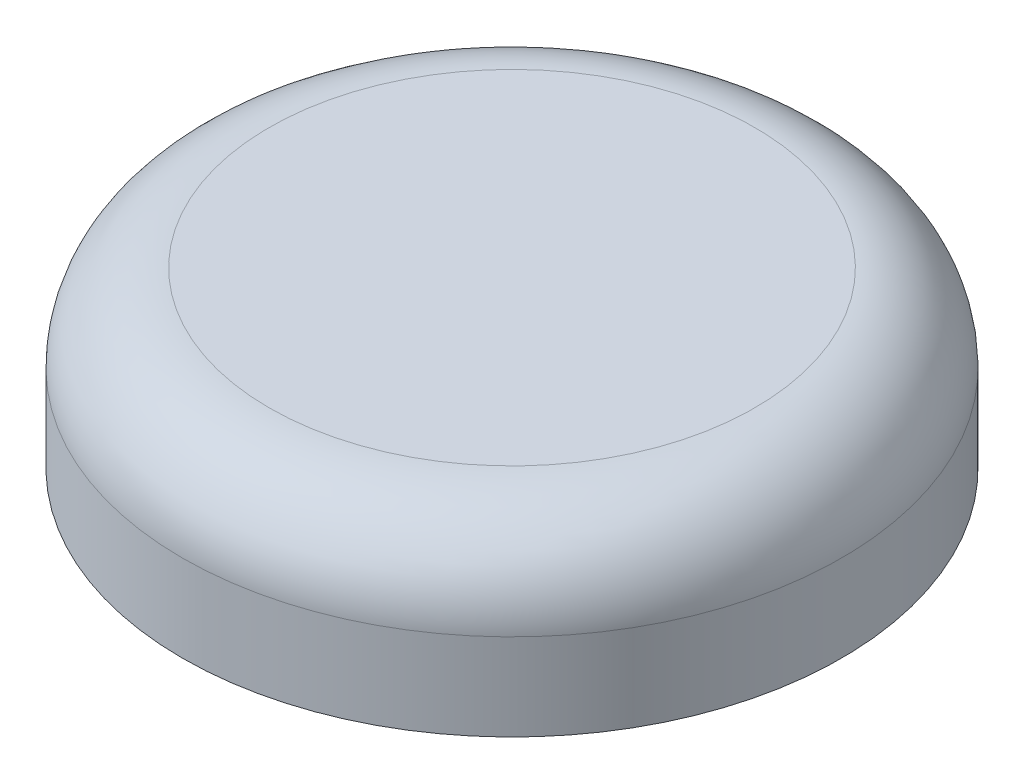
SolidWorks part; units mm, degrees
ref_plane "Front Plane" through (0, 0, 0) normal (0, 0, 1) x (1, 0, 0)
ref_plane "Top Plane" through (0, 0, 0) normal (0, 1, 0) x (1, 0, 0)
ref_plane "Right Plane" through (0, 0, 0) normal (1, 0, 0) x (0, 0, -1)
sketch "Sketch1" plane through (0, 0, 0) normal (0, 1, 0) x (1, 0, 0)
  circle A0 centre (0, 0) radius 28.5
  dimension "D1" = 57
extrude "Boss-Extrude1" add sketch "Sketch1" along normal blind 15
fillet "Fillet1" radius 7.5 1 edges at (0, 15, 28.5)
sketch "Sketch2" plane through (0, 0, 0) normal (0, 1, 0) x (1, 0, 0)
  line L0 (-25.204, 0) -> (24.9636, 0) construction
  line L1 (-16.25, 16.25) -> (16.25, 16.25)
  line L2 (-16.25, 16.25) -> (-16.25, -16.25)
  line L3 (-16.25, -16.25) -> (16.25, -16.25)
  line L4 (16.25, 16.25) -> (16.25, -16.25)
  line L5 (0, 23.5211) -> (0, -23.6012) construction
  point P9 (16.25, 0)
  point P10 (0, 16.25)
  point P11 (0, 0)
  point P12 (0, 0)
  point P13 (0, 0)
  point P14 (0, 0)
  point P15 (0, 0)
  point P16 (0, 0)
  point P17 (0, 0)
  point P18 (0, 0)
  point P19 (0, 0)
  dimension "D1" = 32.5
  dimension "D2" = 32.5
hole_wizard "#32 (0.116) Diameter Hole4" positions "Sketch12" profile "Sketch13" hole size "#32" standard "ANSI Inch"
sketch "Sketch12" plane through (0, 0, 0) normal (0, -1, 0) x (-1, 0, 0)
  point P0 (-16.25, 16.25)
  point P3 (16.25, 16.25)
  point P6 (16.25, -16.25)
  point P9 (-16.25, -16.25)
sketch "Sketch13" plane through (16.25, 0, -16.25) normal (1, 0, 0) x (0, 0, -1)
  line L0 (0, 0) -> (0, 3.8852)
  line L1 (0, 3.8852) -> (1.4732, 3)
  line L2 (1.4732, 3) -> (1.4732, 0)
  line L5 (1.4732, 0) -> (0, 0)
  line L10 (0, 3.8852) -> (-1.4732, 3) construction
  line L11 (0, -6.35) -> (0, 107.95) construction
  dimension "Hole Dia." = 2.9464
  dimension "Hole Depth" = 3
  dimension "Drill Angle" = 118
thread "Thread6" pitch 0.7937 start angle 0, offset 1, length 4, pitch 0.7937, diameter 2.9464
ref_plane "Plane10" through (17.7232, -1, -16.25) normal (0, 0, 1) x (1, 0, 0)
sketch "Thread Profile10" plane through (17.7232, -1, -16.25) normal (0, 0, 1) x (1, 0, 0)
  line L0 (0, 0) -> (0, 0.7937) construction
  line L1 (0, 0) -> (0.4296, 0.248)
  line L2 (0.4296, 0.248) -> (0.4296, 0.3473)
  line L3 (0.4296, 0.3473) -> (0, 0.5953)
  line L4 (0.4296, 0.2977) -> (0, 0.2977) construction
  line L11 (0, 0) -> (0, 0.5953)
  point P2 (0, 0)
  dimension "Pitch" = 0.7937
  dimension "Profile_Angle" = 60
  dimension "Profile_Land" = 0.0992
  dimension "Profile_Height" = 0.4296
thread "Thread7" pitch 0.7937 start angle 0, offset 1, length 4, pitch 0.7937, diameter 2.9464
ref_plane "Plane11" through (-14.7768, -1, -16.25) normal (0, 0, 1) x (1, 0, 0)
sketch "Thread Profile11" plane through (-14.7768, -1, -16.25) normal (0, 0, 1) x (1, 0, 0)
  line L0 (0, 0) -> (0, 0.7937) construction
  line L1 (0, 0) -> (0.4296, 0.248)
  line L2 (0.4296, 0.248) -> (0.4296, 0.3473)
  line L3 (0.4296, 0.3473) -> (0, 0.5953)
  line L4 (0.4296, 0.2977) -> (0, 0.2977) construction
  line L11 (0, 0) -> (0, 0.5953)
  point P2 (0, 0)
  dimension "Pitch" = 0.7937
  dimension "Profile_Angle" = 60
  dimension "Profile_Land" = 0.0992
  dimension "Profile_Height" = 0.4296
thread "Thread8" pitch 0.7937 start angle 0, offset 1, length 4, pitch 0.7937, diameter 2.9464
ref_plane "Plane12" through (-14.7768, -1, 16.25) normal (0, 0, 1) x (1, 0, 0)
sketch "Thread Profile12" plane through (-14.7768, -1, 16.25) normal (0, 0, 1) x (1, 0, 0)
  line L0 (0, 0) -> (0, 0.7937) construction
  line L1 (0, 0) -> (0.4296, 0.248)
  line L2 (0.4296, 0.248) -> (0.4296, 0.3473)
  line L3 (0.4296, 0.3473) -> (0, 0.5953)
  line L4 (0.4296, 0.2977) -> (0, 0.2977) construction
  line L11 (0, 0) -> (0, 0.5953)
  point P2 (0, 0)
  dimension "Pitch" = 0.7937
  dimension "Profile_Angle" = 60
  dimension "Profile_Land" = 0.0992
  dimension "Profile_Height" = 0.4296
thread "Thread9" pitch 0.7937 start angle 0, offset 1, length 4, pitch 0.7937, diameter 2.9464
ref_plane "Plane13" through (17.7232, -1, 16.25) normal (0, 0, 1) x (1, 0, 0)
sketch "Thread Profile13" plane through (17.7232, -1, 16.25) normal (0, 0, 1) x (1, 0, 0)
  line L0 (0, 0) -> (0, 0.7937) construction
  line L1 (0, 0) -> (0.4296, 0.248)
  line L2 (0.4296, 0.248) -> (0.4296, 0.3473)
  line L3 (0.4296, 0.3473) -> (0, 0.5953)
  line L4 (0.4296, 0.2977) -> (0, 0.2977) construction
  line L11 (0, 0) -> (0, 0.5953)
  point P2 (0, 0)
  dimension "Pitch" = 0.7937
  dimension "Profile_Angle" = 60
  dimension "Profile_Land" = 0.0992
  dimension "Profile_Height" = 0.4296
